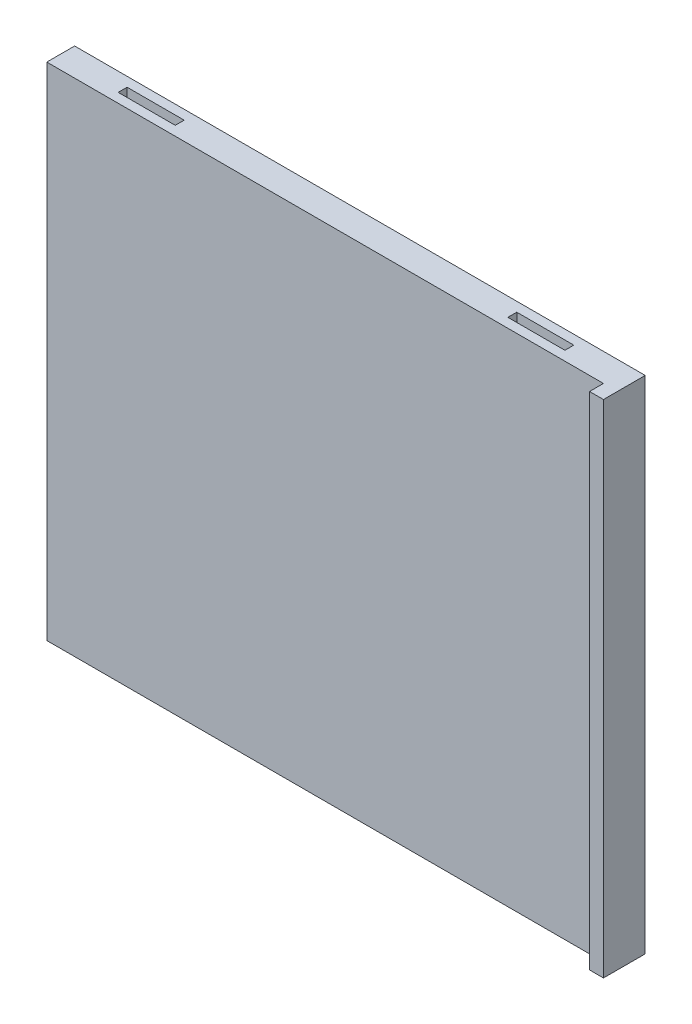
SolidWorks part; units mm, degrees
ref_plane "Front Plane" through (0, 0, 0) normal (1, 0, 0) x (0, 1, 0)
ref_plane "Top Plane" through (0, 0, 0) normal (0, 0, 1) x (0, 1, 0)
ref_plane "Right Plane" through (0, 0, 0) normal (0, 1, 0) x (-1, 0, 0)
sketch "Sketch1" plane through (0, 0, 0) normal (0, 0, 1) x (0, 1, 0)
  line L1 (-90, -102.5) -> (90, -102.5)
  line L2 (-90, -102.5) -> (-90, 102.5)
  line L3 (-90, 102.5) -> (90, 102.5)
  line L4 (90, -102.5) -> (90, 102.5)
  line L5 (-90, -102.5) -> (90, 102.5) construction
  line L6 (-90, 102.5) -> (90, -102.5) construction
  point P0 (0, 0)
  dimension "D1" = 205
  dimension "D2" = 180
extrude "Boss-Extrude1" add sketch "Sketch1" along normal blind 10
sketch "Sketch2" plane through (0, 0, 10) normal (0, 0, 1) x (1, 0, 0)
  line L9 (0, -1000) -> (0, 49000) construction
  line L11 (102.5, 90) -> (102.5, -90)
  line L12 (102.5, -90) -> (97.5, -90)
  line L13 (-102.5, -90) -> (102.5, -90) construction
  line L17 (97.5, -90) -> (97.5, 90)
  line L18 (102.5, 90) -> (-102.5, 90) construction
  line L19 (97.5, 90) -> (102.5, 90)
  dimension "D1" = 5
extrude "Boss-Extrude2" add sketch "Sketch2" along normal blind 5
sketch "Sketch5" plane through (-102.5, 0, 0) normal (-1, 0, 0) x (0, -1, 0)
  line L0 (0, -1000) -> (0, 49000) construction
  line L1 (-90, 0) -> (90, 0) construction
  line L2 (-30, 3.25) -> (-51, 3.25)
  line L3 (-30, 3.25) -> (-30, 6.75)
  line L4 (-30, 6.75) -> (-51, 6.75)
  line L5 (-51, 3.25) -> (-51, 6.75)
  line L6 (-30, 3.25) -> (-51, 6.75) construction
  line L7 (-30, 6.75) -> (-51, 3.25) construction
  line L8 (30, 6.75) -> (51, 3.25) construction
  line L9 (30, 3.25) -> (51, 6.75) construction
  line L10 (51, 3.25) -> (51, 6.75)
  line L11 (30, 6.75) -> (51, 6.75)
  line L12 (30, 3.25) -> (30, 6.75)
  line L13 (30, 3.25) -> (51, 3.25)
  point P1 (-40.5, 5)
  point P14 (40.5, 5)
  dimension "D1" = 21
  dimension "D2" = 3.5
  dimension "D3" = 5
  dimension "D4" = 30
extrude "Cut-Extrude3" cut sketch "Sketch5" against normal blind 10
sketch "Sketch6" plane through (0, -90, 0) normal (0, -1, 0) x (1, 0, 0)
  line L0 (0, -1000) -> (0, 49000) construction
  line L1 (-102.5, 0) -> (102.5, 0) construction
  line L2 (59.75, 3.4) -> (80.25, 3.4)
  line L3 (59.75, 3.4) -> (59.75, 6.6)
  line L4 (59.75, 6.6) -> (80.25, 6.6)
  line L5 (80.25, 3.4) -> (80.25, 6.6)
  line L6 (59.75, 3.4) -> (80.25, 6.6) construction
  line L7 (59.75, 6.6) -> (80.25, 3.4) construction
  line L8 (-59.75, 6.6) -> (-80.25, 3.4) construction
  line L9 (-59.75, 3.4) -> (-80.25, 6.6) construction
  line L10 (-80.25, 3.4) -> (-80.25, 6.6)
  line L11 (-59.75, 6.6) -> (-80.25, 6.6)
  line L12 (-59.75, 3.4) -> (-59.75, 6.6)
  line L13 (-59.75, 3.4) -> (-80.25, 3.4)
  point P1 (70, 5)
  point P15 (-70, 5)
  dimension "D1" = 3.2
  dimension "D2" = 5
  dimension "D3" = 20.5
  dimension "D4" = 70
extrude "Cut-Extrude4" cut sketch "Sketch6" against normal blind 10
mirror "Mirror1" about plane through (0, 0, 0) normal (0, 1, 0) of "Cut-Extrude4"
